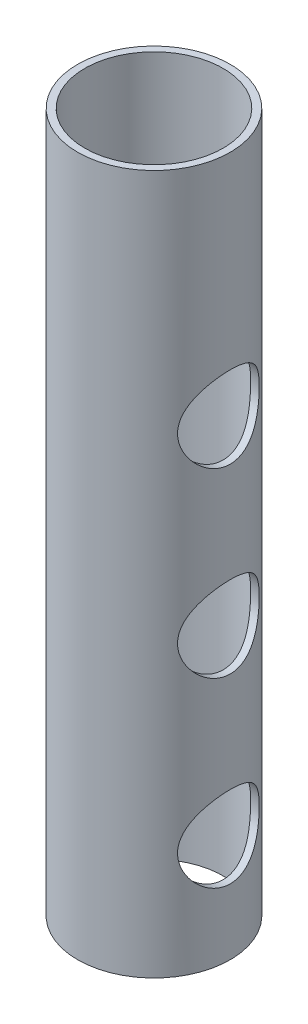
SolidWorks part; units mm, degrees
material "PTFE (general)"
ref_plane "Front Plane" through (0, 0, 0) normal (0, 0, 1) x (1, 0, 0)
ref_plane "Top Plane" through (0, 0, 0) normal (0, 1, 0) x (1, 0, 0)
ref_plane "Right Plane" through (0, 0, 0) normal (1, 0, 0) x (0, 0, -1)
sketch "Sketch1" plane through (0, 0, 0) normal (0, 1, 0) x (1, 0, 0)
  circle A0 centre (0, 0) radius 21.53
  circle A1 centre (0, 0) radius 19.53
  dimension "D1" = 2
  dimension "D2" = 39.06
extrude "Boss-Extrude1" add sketch "Sketch1" along normal blind 197.41
sketch "Sketch2" plane through (0, 0, 0) normal (1, 0, 0) x (0, 0, -1)
  line L0 (19.53, 197.41) -> (-19.53, 197.41) construction
  circle A0 centre (0, 132.71) radius 11.53
  circle A1 centre (0, 81.41) radius 11.53
  circle A2 centre (0, 30.11) radius 11.53
  dimension "D2" = 23.06
  dimension "D3" = 23.06
  dimension "D4" = 23.06
  dimension "D1" = 64.7
  dimension "D5" = 51.3
  dimension "D6" = 51.3
extrude "Cut-Extrude1" cut sketch "Sketch2" along normal through all
